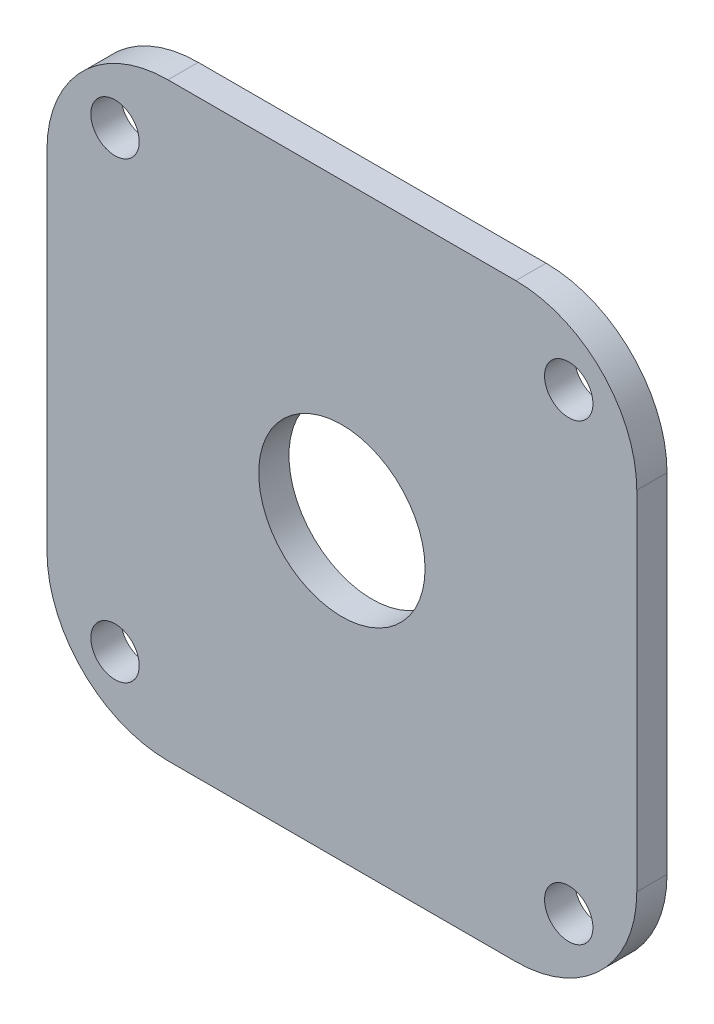
SolidWorks part; units mm, degrees
ref_plane "前视基准面" through (0, 0, 0) normal (0, 0, 1) x (1, 0, 0)
ref_plane "上视基准面" through (0, 0, 0) normal (0, 1, 0) x (1, 0, 0)
ref_plane "右视基准面" through (0, 0, 0) normal (1, 0, 0) x (0, 0, -1)
other "Configuration Table"
sketch "草图1" plane through (0, 0, 0) normal (0, 0, 1) x (1, 0, 0)
  line L1 (-20, -20) -> (20, -20)
  line L2 (-20, -20) -> (-20, 20)
  line L3 (-20, 20) -> (20, 20)
  line L4 (20, -20) -> (20, 20)
  line L5 (-20, -20) -> (20, 20) construction
  line L6 (-20, 20) -> (20, -20) construction
  line L7 (-20, 20) -> (-15, 20)
  line L8 (-20, 20) -> (-20, 15)
  line L9 (-20, 15) -> (-15, 15)
  line L10 (-15, 20) -> (-15, 15)
  line L11 (-19.5, -19.5) -> (19.5, -19.5)
  line L12 (-19.5, -19.5) -> (-19.5, 19.5)
  line L13 (-19.5, 19.5) -> (19.5, 19.5)
  line L14 (19.5, -19.5) -> (19.5, 19.5)
  line L15 (-19.5, -19.5) -> (19.5, 19.5) construction
  line L16 (-19.5, 19.5) -> (19.5, -19.5) construction
  circle A0 centre (0, 0) radius 5.5
  circle A1 centre (-15, 15) radius 1.6
  circle A2 centre (15, 15) radius 1.6
  circle A3 centre (15, -15) radius 1.6
  circle A4 centre (-15, -15) radius 1.6
  point P20 (0, 0)
  dimension "D1" = 11
  dimension "D5" = 3.2
  dimension "D2" = 40
  dimension "D3" = 40
  dimension "D4" = 5
  dimension "D7" = 39
  dimension "D6" = 4
extrude "凸台-拉伸2" add sketch "草图1" along normal blind 2 contours A1 L9 L12 L11 L14 L13 L10 A4 A3 A2 A0 | A1 L10 L13 L12 L9
fillet "圆角6" radius 8 1 edges at (-19.5, 19.5, 1)
fillet "圆角7" radius 8 1 edges at (19.5, 19.5, 1)
fillet "圆角8" radius 8 1 edges at (-19.5, -19.5, 1)
fillet "圆角9" radius 8 1 edges at (19.5, -19.5, 1)
